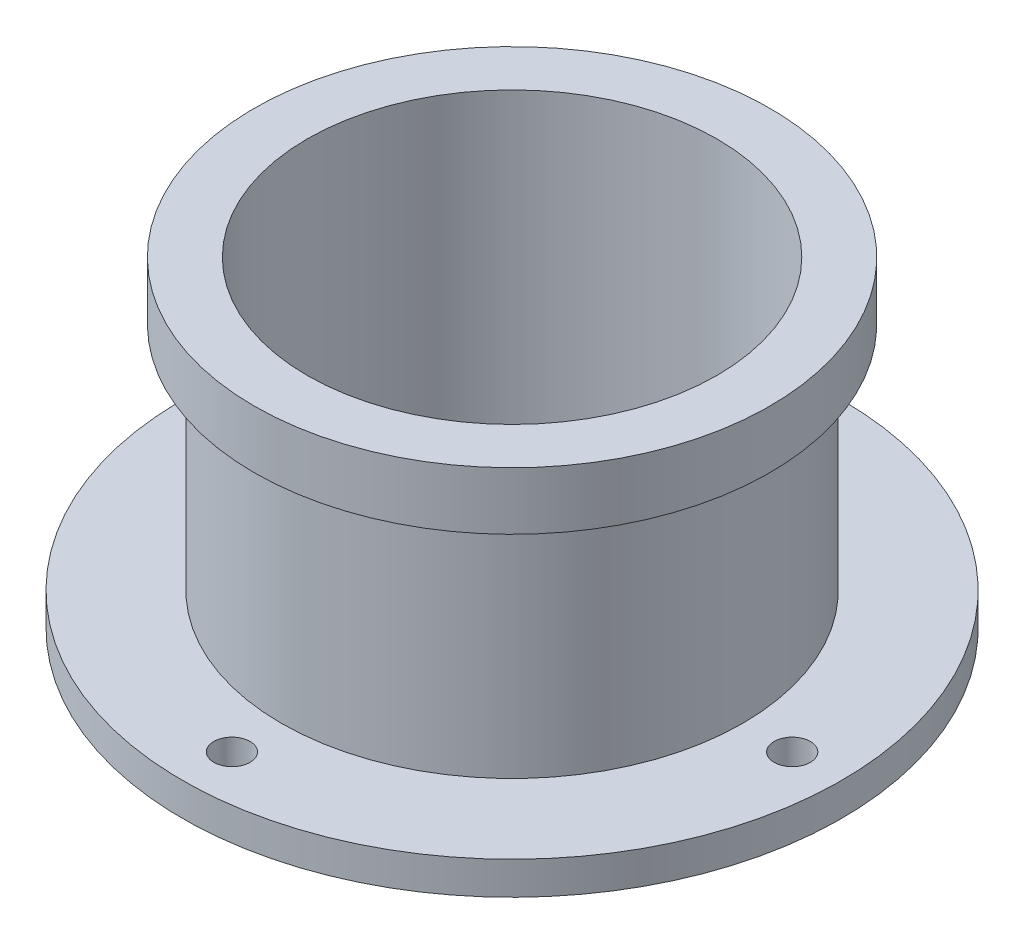
SolidWorks part; units mm, degrees
ref_plane "Front Plane" through (0, 0, 0) normal (0, 0, 1) x (1, 0, 0)
ref_plane "Top Plane" through (0, 0, 0) normal (0, 1, 0) x (1, 0, 0)
ref_plane "Right Plane" through (0, 0, 0) normal (1, 0, 0) x (0, 0, -1)
sketch "Sketch1" plane through (0, 0, 0) normal (0, 1, 0) x (1, 0, 0)
  circle A0 centre (0, 0) radius 39.125
  dimension "D1" = 78.25
extrude "Boss-Extrude1" add sketch "Sketch1" along normal blind 8.75
sketch "Sketch4" plane through (0, 0, 0) normal (0, -1, 0) x (1, 0, 0)
  circle A0 centre (0, 0) radius 31.0832
extrude "Cut-Extrude1" cut sketch "Sketch4" against normal blind 9
sketch "Sketch5" plane through (0, 0, 0) normal (0, -1, 0) x (1, 0, 0)
  circle A0 centre (0, 0) radius 35
  circle A1 centre (0, 0) radius 31.0832
  dimension "D1" = 70
  dimension "D2" = 62.1664
extrude "Boss-Extrude3" add sketch "Sketch5" along normal blind 40
sketch "Sketch8" plane through (0, -40, 0) normal (0, -1, 0) x (1, 0, 0)
  circle A1 centre (0, 0) radius 50
  circle A4 centre (0, 0) radius 35 construction
  dimension "D1" = 15
extrude "Boss-Extrude4" add sketch "Sketch8" against normal blind 5
sketch "Sketch10" plane through (0, -35, 0) normal (0, 1, 0) x (1, 0, 0)
  circle A0 centre (0, 42.5) radius 2.75
  circle A1 centre (0, 0) radius 42.5 construction
  circle A2 centre (0, 0) radius 50 construction
  circle A3 centre (42.5, 0) radius 2.75
  circle A4 centre (0, -42.5) radius 2.75
  circle A5 centre (-42.5, 0) radius 2.75
  point P16 (0, 0)
  dimension "D1" = 5.5
  dimension "D2" = 7.5
  dimension "D3" = 4
extrude "Cut-Extrude2" cut sketch "Sketch10" against normal blind 5
sketch "Sketch11" plane through (0, -35, 0) normal (0, 1, 0) x (1, 0, 0)
  circle A0 centre (0, 0) radius 31.0832
extrude "Cut-Extrude3" cut sketch "Sketch11" against normal blind 5
